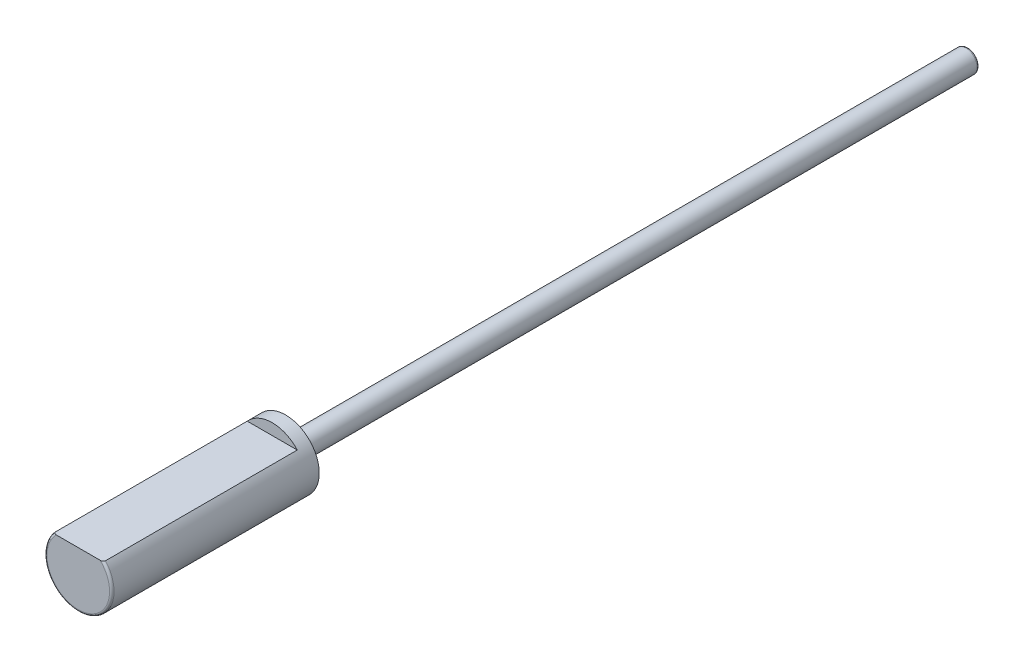
SolidWorks part; units mm, degrees
material "6061 Alloy"
ref_plane "Front Plane" through (0, 0, 0) normal (0, 0, 1) x (1, 0, 0)
ref_plane "Top Plane" through (0, 0, 0) normal (0, 1, 0) x (1, 0, 0)
ref_plane "Right Plane" through (0, 0, 0) normal (1, 0, 0) x (0, 0, -1)
sketch "Sketch1" plane through (0, 0, 0) normal (0, 0, 1) x (1, 0, 0)
  circle A0 centre (0, 0) radius 1.5
  dimension "D1" = 3
extrude "Boss-Extrude1" add sketch "Sketch1" against normal blind 9.27
sketch "Sketch2" plane through (0, 0, 0) normal (0, 0, 1) x (1, 0, 0)
  line L0 (-1.118, 1) -> (1.118, 1)
  circle A0 centre (0, 0) radius 1.5 construction
  arc A1 (1.118, 1) -> (-1.118, 1) centre (0, 0) ccw
  dimension "D1" = 1
extrude "Cut-Extrude1" cut sketch "Sketch2" against normal blind 8.67
sketch "Sketch3" plane through (0, 0, -9.27) normal (0, 0, -1) x (-1, 0, 0)
  circle A0 centre (0, 0) radius 0.5
  dimension "D1" = 1
extrude "Boss-Extrude2" add sketch "Sketch3" along normal blind 30.5
fillet "Fillet1" radius 0.1 2 edges at (-0.5, 0, -39.77) (0, -1.5, 0)
